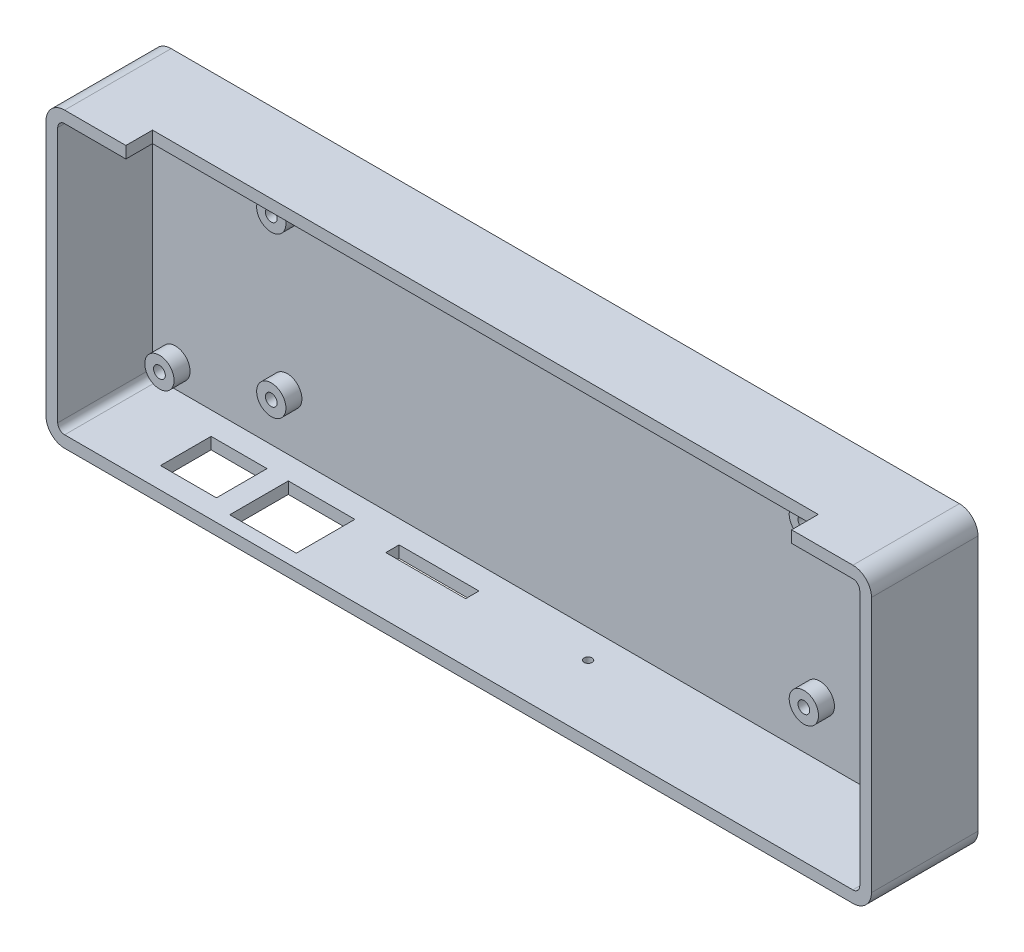
SolidWorks part; units mm, degrees
ref_plane "前视基准面" through (0, 0, 0) normal (0, 0, 1) x (1, 0, 0)
ref_plane "上视基准面" through (0, 0, 0) normal (0, 1, 0) x (1, 0, 0)
ref_plane "右视基准面" through (0, 0, 0) normal (1, 0, 0) x (0, 0, -1)
other "Configuration Table"
sketch "草图1" plane through (0, 0, 0) normal (0, 0, 1) x (1, 0, 0)
  line L1 (0, 0) -> (155, 0)
  line L2 (0, 0) -> (0, -55)
  line L3 (0, -55) -> (155, -55)
  line L4 (155, 0) -> (155, -55)
  dimension "D1" = 155
  dimension "D2" = 55
extrude "凸台-拉伸1" add sketch "草图1" along normal blind 20
fillet "圆角1" radius 3.5 4 edges at (0, 0, 10) (0, -55, 10) (155, 0, 10) (155, -55, 10)
shell "抽壳1" thickness 2.2
sketch "草图2" plane through (0, 0, 2.2) normal (0, 0, 1) x (1, 0, 0)
  line L0 (151.5, 0) -> (3.5, 0) construction
  line L1 (0, -3.5) -> (0, -51.5) construction
  circle A0 centre (27.5, -12.5) radius 1.1
  circle A2 centre (127.5, -12.5) radius 1.1
  circle A3 centre (127.5, -42.5) radius 1.1
  circle A4 centre (27.5, -42.5) radius 1.1
  dimension "D1" = 2.2
  dimension "D2" = 12.5
  dimension "D3" = 27.5
  dimension "D4" = 2
  dimension "D5" = 2
extrude "切除-拉伸1" cut sketch "草图2" against normal blind 10
sketch "草图3" plane through (0, 0, 2.2) normal (0, 0, 1) x (1, 0, 0)
  line L0 (0, -3.5) -> (0, -51.5) construction
  line L1 (151.5, 0) -> (3.5, 0) construction
  circle A0 centre (27.5, -12.5) radius 2.75
  circle A1 centre (27.5, -12.5) radius 1.1 construction
  circle A2 centre (27.5, -12.5) radius 1.1
  circle A3 centre (127.5, -12.5) radius 1.1
  circle A4 centre (127.5, -12.5) radius 2.75
  circle A5 centre (127.5, -42.5) radius 1.1
  circle A6 centre (127.5, -42.5) radius 2.75
  circle A7 centre (27.5, -42.5) radius 1.1
  circle A8 centre (27.5, -42.5) radius 2.75
  circle A9 centre (6.5, -6.5) radius 2.75
  circle A10 centre (6.5, -6.5) radius 1.1
  circle A11 centre (148.5, -6.5) radius 1.1
  circle A12 centre (148.5, -6.5) radius 2.75
  circle A13 centre (148.5, -48.5) radius 1.1
  circle A14 centre (148.5, -48.5) radius 2.75
  circle A15 centre (6.5, -48.5) radius 1.1
  circle A16 centre (6.5, -48.5) radius 2.75
  dimension "D1" = 5.5
  dimension "D4" = 5.5
  dimension "D7" = 2.2
  dimension "D5" = 6.5
  dimension "D6" = 6.5
  dimension "D2" = 2
  dimension "D3" = 2
  dimension "D8" = 2
  dimension "D9" = 2
extrude "凸台-拉伸2" add sketch "草图3" along normal blind 3
sketch "草图4" plane through (0, -55, 0) normal (0, -1, 0) x (1, 0, 0)
  line L1 (17.5, 16) -> (28, 16)
  line L2 (17.5, 16) -> (17.5, 6.5)
  line L3 (17.5, 6.5) -> (28, 6.5)
  line L4 (28, 16) -> (28, 6.5)
  line L5 (3.5, 0) -> (151.5, 0) construction
  line L6 (32, 17.5) -> (44.5, 17.5)
  line L7 (32, 17.5) -> (32, 6.5)
  line L8 (32, 6.5) -> (44.5, 6.5)
  line L9 (44.5, 17.5) -> (44.5, 6.5)
  line L10 (52.8, 9) -> (67.8, 9)
  line L11 (52.8, 9) -> (52.8, 6.5)
  line L12 (52.8, 6.5) -> (67.8, 6.5)
  line L13 (67.8, 9) -> (67.8, 6.5)
  line L14 (0, 0) -> (0, 20) construction
  circle A0 centre (89.3, 7.5) radius 0.75
  dimension "D13" = 1.5
  dimension "D1" = 2.5
  dimension "D2" = 15
  dimension "D3" = 11
  dimension "D4" = 12.5
  dimension "D5" = 9.5
  dimension "D6" = 10.5
  dimension "D7" = 6.5
  dimension "D8" = 17.5
  dimension "D9" = 4
  dimension "D10" = 8.3
  dimension "D11" = 21.5
  dimension "D12" = 7.5
extrude "切除-拉伸2" cut sketch "草图4" against normal blind 3
sketch "草图5" plane through (0, 0, 0) normal (0, 1, 0) x (1, 0, 0)
  line L0 (151.5, -20) -> (3.5, -20) construction
  line L1 (15, -20) -> (140, -20)
  line L2 (15, -20) -> (15, -15)
  line L3 (15, -15) -> (140, -15)
  line L12 (140, -20) -> (140, -15)
  line L13 (155, 0) -> (155, -20) construction
  line L14 (0, -20) -> (0, 0) construction
  dimension "D1" = 5
  dimension "D2" = 15
  dimension "D3" = 15
extrude "切除-拉伸3" cut sketch "草图5" against normal blind 3
